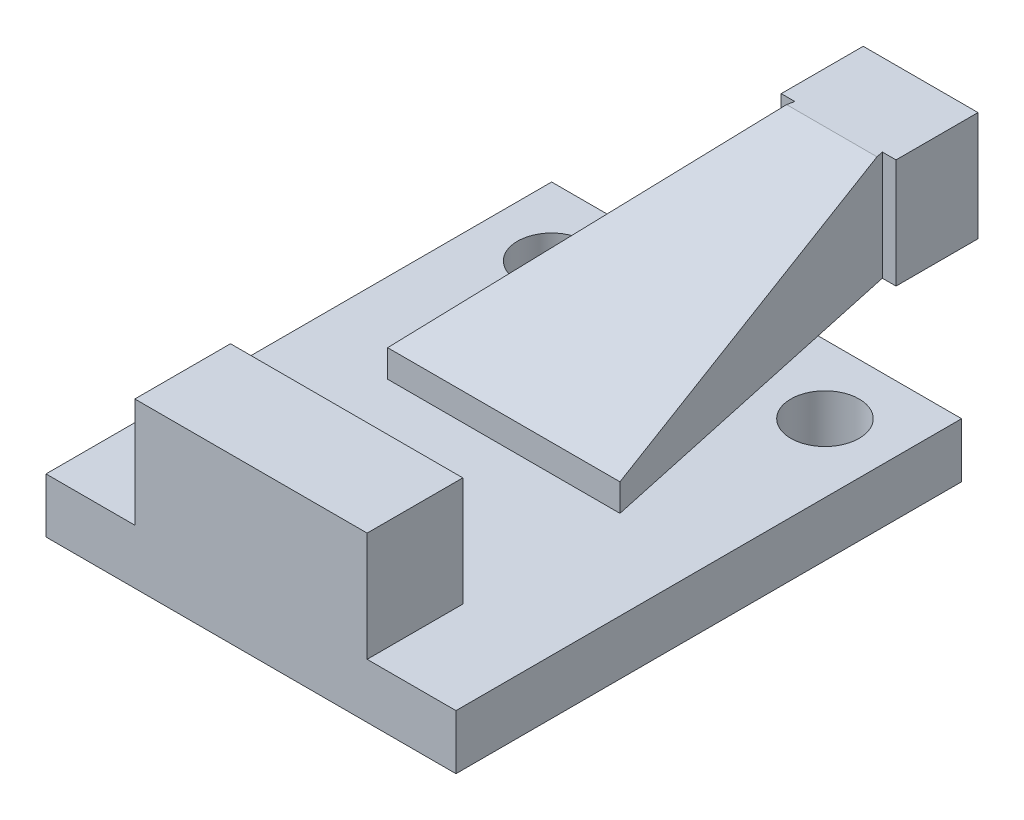
SolidWorks part; units mm, degrees
ref_plane "Front Plane" through (0, 0, 0) normal (0, 0, 1) x (1, 0, 0)
ref_plane "Top Plane" through (0, 0, 0) normal (0, 1, 0) x (1, 0, 0)
ref_plane "Right Plane" through (0, 0, 0) normal (1, 0, 0) x (0, 0, -1)
sketch "Sketch1" plane through (0, 0, 0) normal (0, 1, 0) x (1, 0, 0)
  line L0 (2.5, 16) -> (2.5, 18.5) construction
  line L1 (0, 18.5) -> (15, 18.5)
  line L2 (0, 18.5) -> (0, 0)
  line L3 (0, 0) -> (15, 0)
  line L4 (15, 18.5) -> (15, 0)
  line L5 (-135.5886, -91.8289) -> (-269.7548, 54.5878) construction
  line L6 (7.5, 18.5) -> (7.5, 0) construction
  line L7 (0, 16) -> (2.5, 16) construction
  circle A0 centre (2.5, 16) radius 1.25
  circle A1 centre (12.5, 16) radius 1.25
  dimension "D3" = 2.5
  dimension "D1" = 18.5
  dimension "D2" = 15
  dimension "D4" = 2.5
extrude "Boss-Extrude1" add sketch "Sketch1" along normal blind 2
sketch "Sketch2" plane through (0, 2, 0) normal (0, 1, 0) x (1, 0, 0)
  line L0 (-367.4284, 11.4979) -> (-514.1728, 476.9118) construction
  line L1 (0, 0) -> (15, 0) construction
  line L2 (3.25, 3.5) -> (11.75, 3.5)
  line L3 (3.25, 3.5) -> (3.25, 0)
  line L4 (3.25, 0) -> (11.75, 0)
  line L5 (11.75, 3.5) -> (11.75, 0)
  line L6 (15, 18.5) -> (0, 18.5) construction
  line L7 (3.25, 24.5) -> (11.75, 24.5) construction
  line L8 (3.25, 24.5) -> (3.25, 9.25) construction
  line L9 (3.25, 9.25) -> (11.75, 9.25)
  line L10 (11.75, 24.5) -> (11.75, 9.25) construction
  line L11 (0, 18.5) -> (0, 0) construction
  line L12 (5.9, 21.5) -> (3.25, 9.25)
  line L13 (5.4, 24.5) -> (9.6, 24.5)
  line L14 (5.4, 24.5) -> (5.4, 21.5)
  line L15 (5.4, 21.5) -> (5.9, 21.5)
  line L16 (9.6, 24.5) -> (9.6, 21.5)
  line L17 (11.75, 9.25) -> (9.1, 21.5)
  line L18 (7.5, 24.5) -> (7.5, 9.25) construction
  line L19 (9.1, 21.5) -> (9.6, 21.5)
  point P12 (7.5, 18.5)
  point P13 (7.5, 24.5)
  point P16 (7.5, 3.5)
  point P19 (0, 9.25)
  dimension "D1" = 8.5
  dimension "D2" = 3.5
  dimension "D3" = 6
  dimension "D4" = 4.2
  dimension "D5" = 3
  dimension "D6" = 0.5
extrude "Boss-Extrude2" add sketch "Sketch2" along normal blind 4
chamfer "Chamfer1" distance 3 distance2 12 1 edges at (7.5, 6, -9.25)
